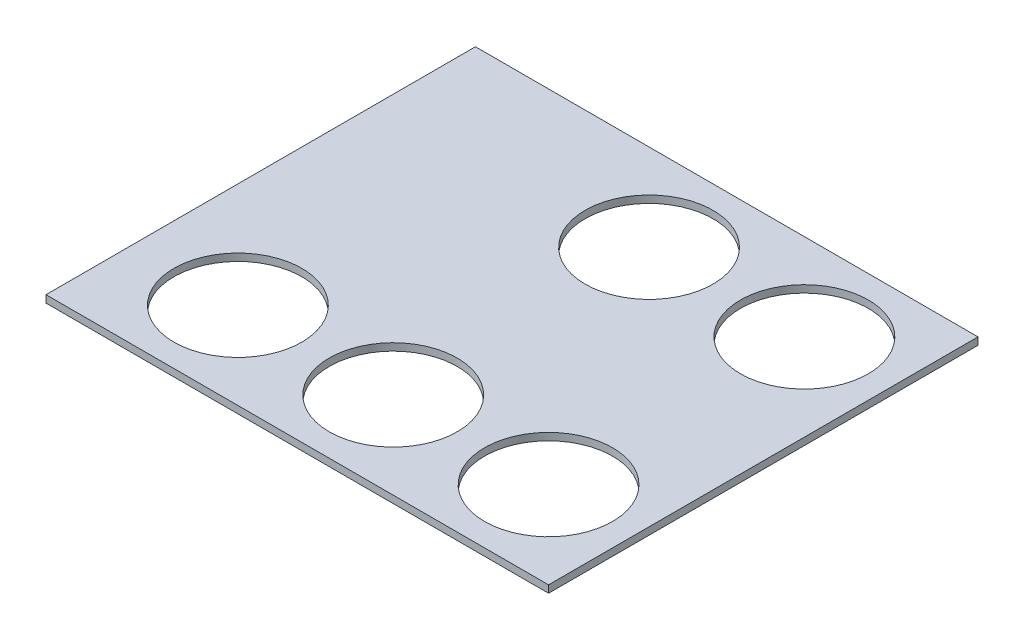
SolidWorks part; units mm, degrees
ref_plane "Front Plane" through (0, 0, 0) normal (0, 0, 1) x (1, 0, 0)
ref_plane "Top Plane" through (0, 0, 0) normal (0, 1, 0) x (1, 0, 0)
ref_plane "Right Plane" through (0, 0, 0) normal (1, 0, 0) x (0, 0, -1)
sketch "Sketch1" plane through (0, 0, 0) normal (0, 1, 0) x (1, 0, 0)
  line L1 (0, 0) -> (550, 0)
  line L2 (0, 0) -> (0, 470)
  line L3 (0, 470) -> (550, 470)
  line L4 (550, 0) -> (550, 470)
  circle A0 centre (111.6535, 251.8334) radius 53.1662 construction
  dimension "D1" = 550
  dimension "D2" = 470
extrude "Boss-Extrude1" add sketch "Sketch1" along normal blind 8
sketch "Sketch2" plane through (0, 0, 0) normal (0, 1, 0) x (1, 0, 0)
  line L0 (0, 0) -> (550, 0) construction
  line L1 (550, 0) -> (550, 470) construction
  line L2 (550, 470) -> (0, 470) construction
  circle A0 centre (455, 95) radius 70
  circle A1 centre (285, 95) radius 70
  circle A2 centre (115, 95) radius 70
  circle A3 centre (455, 375) radius 70
  circle A4 centre (285, 375) radius 70
  dimension "D2" = 140
  dimension "D3" = 95
  dimension "D8" = 140
  dimension "D10" = 140
  dimension "D11" = 140
  dimension "D12" = 140
  dimension "D4" = 95
  dimension "D5" = 170
  dimension "D6" = 95
  dimension "D7" = 170
  dimension "D9" = 95
  dimension "D13" = 95
  dimension "D14" = 95
  dimension "D15" = 95
  dimension "D16" = 170
extrude "Cut-Extrude5" cut sketch "Sketch2" along normal blind 8
